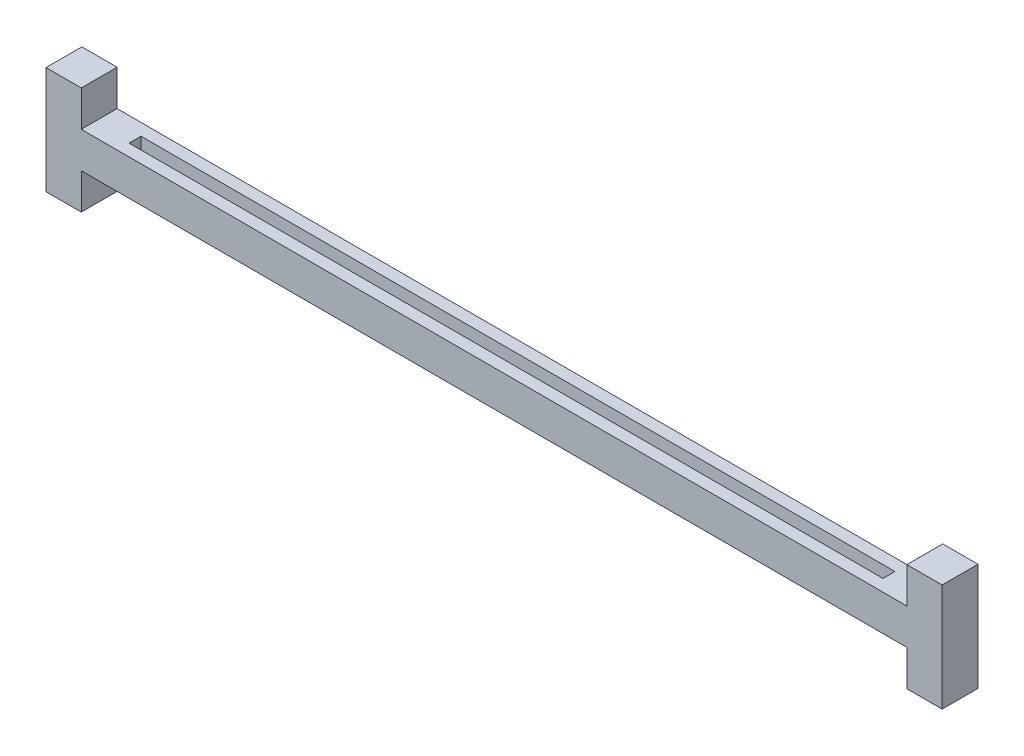
SolidWorks part; units mm, degrees
ref_plane "Front Plane" through (0, 0, 0) normal (0, 0, 1) x (1, 0, 0)
ref_plane "Top Plane" through (0, 0, 0) normal (0, 1, 0) x (1, 0, 0)
ref_plane "Right Plane" through (0, 0, 0) normal (1, 0, 0) x (0, 0, -1)
sketch "Sketch1" plane through (0, 0, 0) normal (0, 0, 1) x (1, 0, 0)
  line L0 (-57.58, 7.5) -> (-57.58, 2.5)
  line L1 (-62.5, 7.5) -> (-57.58, 7.5)
  line L2 (-62.5, 7.5) -> (-62.5, -7.5)
  line L3 (-62.5, -7.5) -> (-57.58, -7.5)
  line L4 (62.5, 7.5) -> (62.5, -7.5)
  line L5 (57.58, 7.5) -> (57.58, 2.5)
  line L6 (57.58, -7.5) -> (62.5, -7.5)
  line L7 (-57.58, 2.5) -> (57.58, 2.5)
  line L9 (-57.58, -2.5) -> (57.58, -2.5)
  line L11 (57.58, 7.5) -> (62.5, 7.5)
  line L12 (-57.58, -2.5) -> (-57.58, -7.5)
  line L13 (57.58, -2.5) -> (57.58, -7.5)
  line L14 (-62.5, 7.5) -> (62.5, -7.5) construction
  line L15 (62.5, 7.5) -> (-62.5, -7.5) construction
  point P12 (0, 0)
  dimension "D1" = 4.92
  dimension "D2" = 4.92
  dimension "D3" = 5
  dimension "D4" = 5
  dimension "D5" = 15
  dimension "D6" = 125
extrude "Slider Main Body" add sketch "Sketch1" along normal blind 5
sketch "Sketch4" plane through (0, -2.5, 0) normal (0, -1, 0) x (1, 0, 0)
  line L0 (52.58, 5) -> (52.58, 0)
  line L1 (-57.58, 5) -> (57.58, 5) construction
  line L2 (-57.58, 0) -> (57.58, 0) construction
  line L3 (57.58, 5) -> (57.58, 0) construction
  line L5 (-52.58, 3.3333) -> (52.58, 3.3333)
  line L7 (-52.58, 1.6667) -> (52.58, 1.6667)
  line L8 (52.58, 3.3333) -> (52.58, 1.6667)
  line L10 (-57.58, 5) -> (-57.58, 0) construction
  line L11 (-57.58, 5) -> (-57.58, 0)
  line L12 (-52.58, 5) -> (-52.58, 0)
  line L13 (-57.58, 5) -> (-52.58, 5)
  line L14 (-52.58, 0) -> (-57.58, 0)
  point P12 (0, 0)
  point P14 (0, 0)
  dimension "D4" = 5
  dimension "D1" = 5
  dimension "D2" = 1.6667
  dimension "D3" = 1.6667
extrude "Cut-Extrude1" cut sketch "Sketch4" against normal through all contours L5 L12 L7 L0
equation "\"Frame side length\"= \"Useful Tray Size\" + \"Universal Bar Height\" * 3"
equation "\"Universal Bar Height\"= 5mm"
equation "\"D1@Sketch1\"=\"Universal Bar Height\" - \"Slider Tolerance\"/2"
equation "\"D2@Sketch1\"=\"Universal Bar Height\" - \"Slider Tolerance\"/2"
equation "\"D3@Sketch1\"=\"Universal Bar Height\""
equation "\"D4@Sketch1\"=\"Universal Bar Height\""
equation "\"D5@Sketch1\"=\"Universal Bar Height\"*3"
equation "\"D6@Sketch1\"=\"Universal Bar Height\"*2 +\"Frame side length\""
equation "\"D1@Slider Main Body\" = \"Universal Bar Height\""
equation "\"Useful Tray Size\"= 100mm"
equation "\"D1@Sketch4\"=\"Universal Bar Height\""
equation "\"D2@Sketch4\"=\"Universal Bar Height\"/3"
equation "\"D3@Sketch4\"=\"Universal Bar Height\"/3"
equation "\"D4@Sketch4\"=\"Universal Bar Height\""
equation "\"Slider Tolerance\"= 0.16mm'The total extra width on the inside of the slider, so it won't grip the frame too much"
